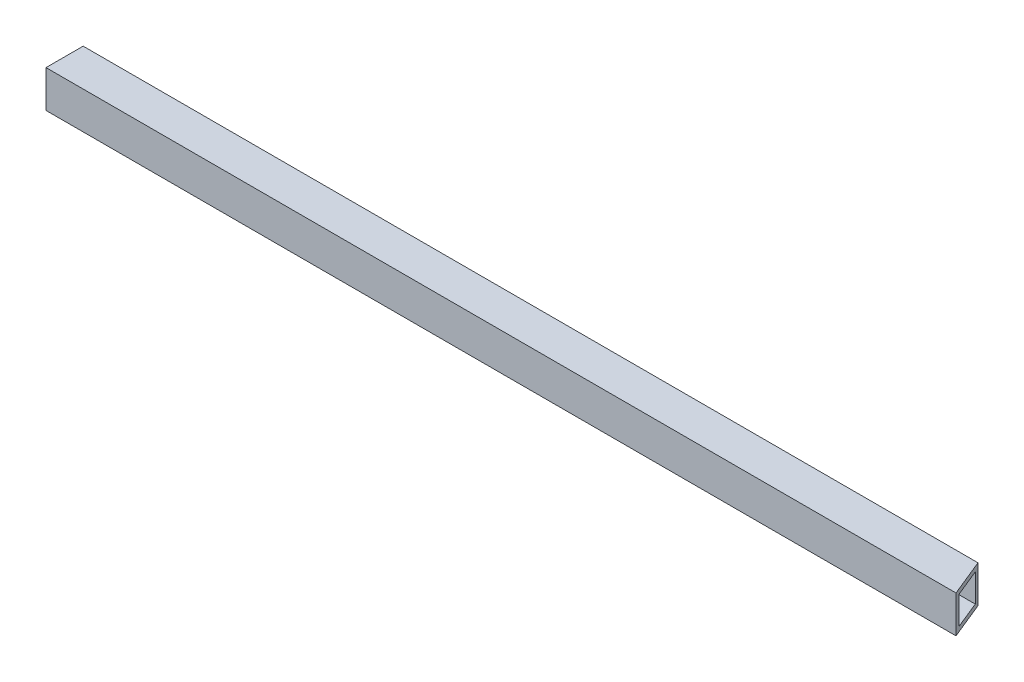
SolidWorks part; units mm, degrees
ref_plane "Front Plane" through (0, 0, 0) normal (0, 0, 1) x (1, 0, 0)
ref_plane "Top Plane" through (0, 0, 0) normal (0, 1, 0) x (1, 0, 0)
ref_plane "Right Plane" through (0, 0, 0) normal (1, 0, 0) x (0, 0, -1)
sketch "Sketch2" plane through (0, 0, 0) normal (1, 0, 0) x (0, 0, -1)
  line L1 (-12.7, 12.7) -> (12.7, 12.7)
  line L2 (-12.7, 12.7) -> (-12.7, -12.7)
  line L3 (-12.7, -12.7) -> (12.7, -12.7)
  line L4 (12.7, 12.7) -> (12.7, -12.7)
  line L5 (-12.7, 12.7) -> (12.7, -12.7) construction
  line L6 (-12.7, -12.7) -> (12.7, 12.7) construction
  line L7 (-9.525, -9.525) -> (9.525, -9.525)
  line L8 (-9.525, -9.525) -> (-9.525, 9.525)
  line L9 (-9.525, 9.525) -> (9.525, 9.525)
  line L10 (9.525, -9.525) -> (9.525, 9.525)
  line L11 (-9.525, -9.525) -> (9.525, 9.525) construction
  line L12 (-9.525, 9.525) -> (9.525, -9.525) construction
  point P0 (0, 0)
  point P6 (0, 0)
  dimension "D1" = 25.4
  dimension "D2" = 25.4
  dimension "D3" = 19.05
extrude "Boss-Extrude1" add sketch "Sketch2" along normal blind 622.3
sketch "Sketch3" plane through (0, 12.7, 0) normal (0, 1, 0) x (1, 0, 0)
  line L0 (622.3, -12.7) -> (611.9388, 12.7)
  line L1 (622.3, 12.7) -> (0, 12.7) construction
  line L2 (611.9388, 12.7) -> (622.3, 12.7)
  line L3 (622.3, 12.7) -> (622.3, -12.7)
  dimension "D1" = 27.432
extrude "Cut-Extrude1" cut sketch "Sketch3" against normal up to surface (25.4 mm away) up to face at (311.15, -12.7, 0)
